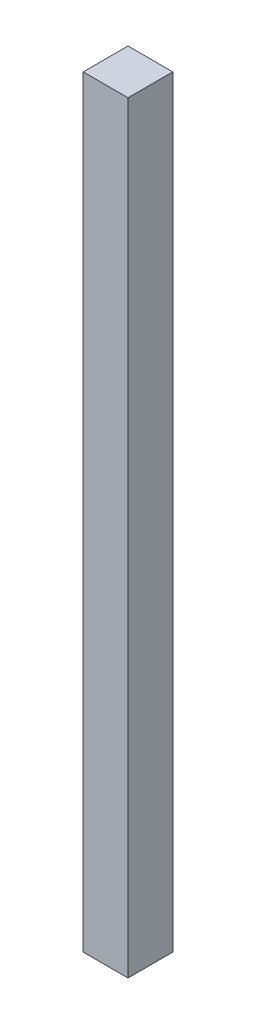
SolidWorks part; units mm, degrees
material "Concreto"
ref_plane "Plano frontal" through (0, 0, 0) normal (0, 0, 1) x (1, 0, 0)
ref_plane "Plano superior" through (0, 0, 0) normal (0, 1, 0) x (1, 0, 0)
ref_plane "Plano direito" through (0, 0, 0) normal (1, 0, 0) x (0, 0, -1)
sketch "Esboço1" plane through (0, 0, 0) normal (0, 1, 0) x (1, 0, 0)
  line L1 (-50, 50) -> (50, 50)
  line L2 (-50, 50) -> (-50, -50)
  line L3 (-50, -50) -> (50, -50)
  line L4 (50, 50) -> (50, -50)
  line L5 (-50, 50) -> (50, -50) construction
  line L6 (-50, -50) -> (50, 50) construction
  point P0 (0, 0)
  dimension "D1" = 100
  dimension "D2" = 100
extrude "Ressalto-extrusão1" add sketch "Esboço1" along normal blind 1700
